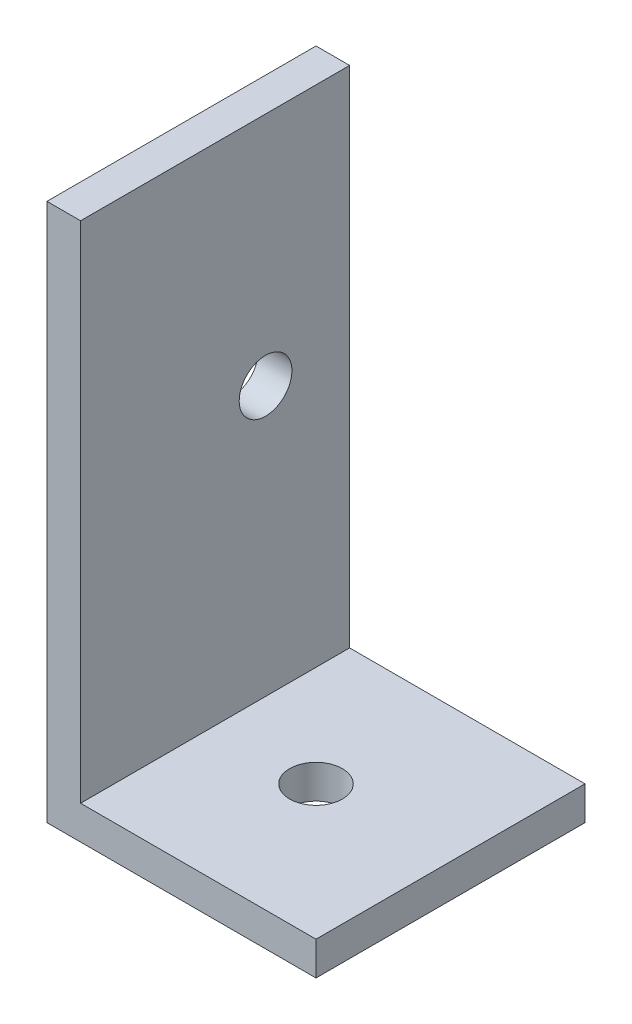
SolidWorks part; units mm, degrees
ref_plane "Front Plane" through (0, 0, 0) normal (0, 0, 1) x (1, 0, 0)
ref_plane "Top Plane" through (0, 0, 0) normal (0, 1, 0) x (1, 0, 0)
ref_plane "Right Plane" through (0, 0, 0) normal (1, 0, 0) x (0, 0, -1)
sketch "Sketch1" plane through (0, 0, 0) normal (0, 0, 1) x (1, 0, 0)
  line L0 (0, 0) -> (0, 50.8)
  line L1 (0, 50.8) -> (3.175, 50.8)
  line L2 (3.175, 50.8) -> (3.175, 3.175)
  line L3 (3.175, 3.175) -> (25.4, 3.175)
  line L4 (25.4, 3.175) -> (25.4, 0)
  line L5 (25.4, 0) -> (0, 0)
  dimension "D1" = 3.175
  dimension "D2" = 50.8
  dimension "D3" = 25.4
extrude "Boss-Extrude1" add sketch "Sketch1" along normal mid plane 25.4
sketch "Sketch2" plane through (0, 3.175, 0) normal (0, 1, 0) x (1, 0, 0)
  line L1 (0, -12.7) -> (25.4, -12.7) construction
  line L2 (25.4, -12.7) -> (25.4, 12.7) construction
  circle A0 centre (12.7, 0) radius 2.4892
  point P4 (12.7, -12.7)
  point P7 (25.4, 0)
  dimension "D1" = 4.9784
extrude "Cut-Extrude1" cut sketch "Sketch2" against normal through all
sketch "Sketch3" plane through (3.175, 0, 0) normal (1, 0, 0) x (0, 0, -1)
  line L1 (12.7, 3.175) -> (12.7, 50.8) construction
  line L2 (-12.7, 0) -> (12.7, 0) construction
  circle A0 centre (4.7625, 28.575) radius 2.4892
  point P6 (7.7515, 3.4073)
  dimension "D1" = 4.9784
  dimension "D3" = 28.575
  dimension "D2" = 7.9375
extrude "Cut-Extrude2" cut sketch "Sketch3" against normal through all
